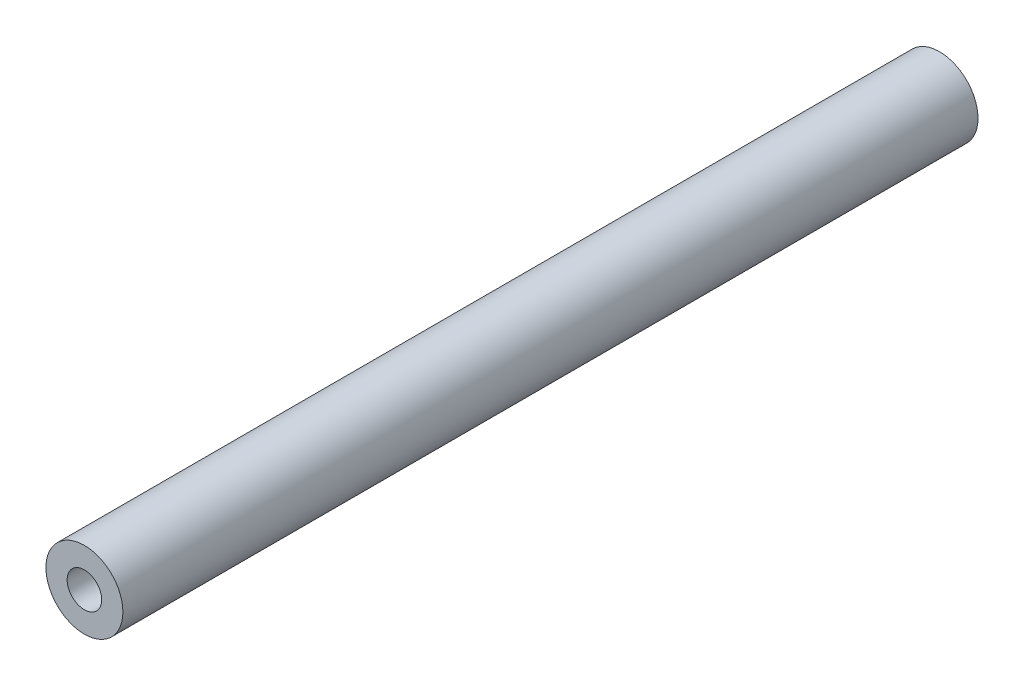
SolidWorks part; units mm, degrees
ref_plane "前视基准面" through (0, 0, 0) normal (0, 0, 1) x (1, 0, 0)
ref_plane "上视基准面" through (0, 0, 0) normal (0, 1, 0) x (1, 0, 0)
ref_plane "右视基准面" through (0, 0, 0) normal (1, 0, 0) x (0, 0, -1)
other "Configuration Table"
sketch "Sketch_Expansion_column" plane through (0, 0, 0) normal (0, 0, 1) x (1, 0, 0)
  circle A0 centre (0, 0) radius 4.5
  dimension "D1" = 9
extrude "Expansion_column" add sketch "Sketch_Expansion_column" along normal blind 100 from offset 0
sketch "Sketch_M4_thread_envelope" plane through (0, 0, 0) normal (0, 0, 1) x (1, 0, 0)
  circle A0 centre (0, 0) radius 2.02
  dimension "D1" = 4.04
extrude "M4_thread_envelope" cut sketch "Sketch_M4_thread_envelope" along normal blind 102 from offset 1
